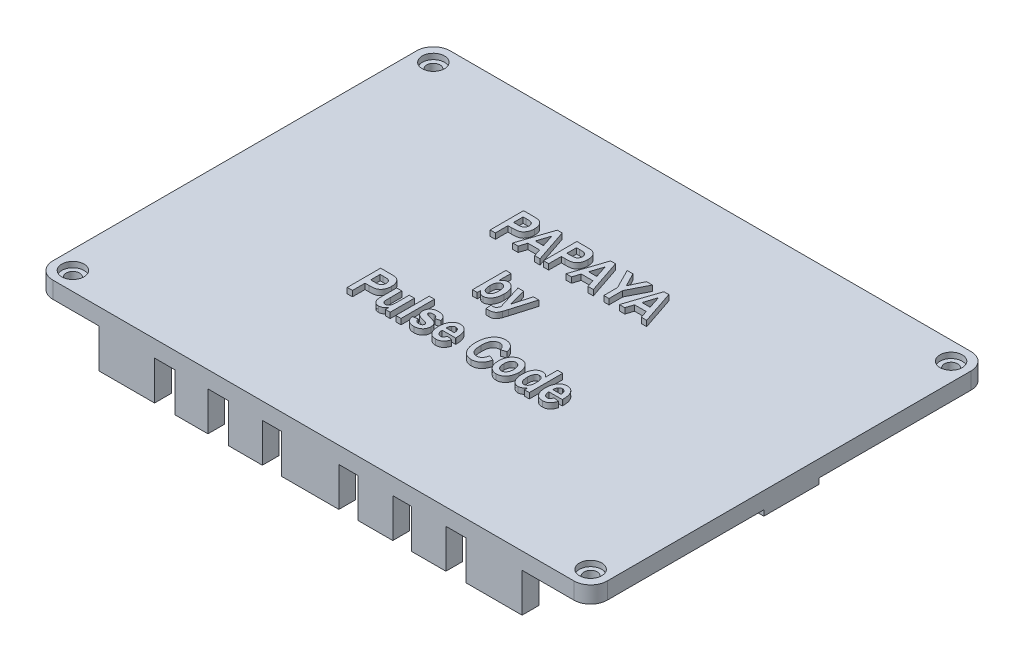
SolidWorks part; units mm, degrees
ref_plane "Front Plane" through (0, 0, 0) normal (0, 0, 1) x (1, 0, 0)
ref_plane "Top Plane" through (0, 0, 0) normal (0, 1, 0) x (1, 0, 0)
ref_plane "Right Plane" through (0, 0, 0) normal (1, 0, 0) x (0, 0, -1)
sketch "Sketch1" plane through (0, 0, 0) normal (0, 1, 0) x (1, 0, 0)
  line L0 (-48.075, 35.695) -> (-51.575, 35.695)
  line L1 (-48.075, 35.695) -> (48.075, 35.695)
  line L3 (-48.075, -35.695) -> (48.075, -35.695)
  line L4 (48.075, 35.695) -> (48.075, -35.695)
  line L5 (-48.075, 35.695) -> (48.075, -35.695) construction
  line L6 (-48.075, -35.695) -> (48.075, 35.695) construction
  line L7 (-51.575, 35.695) -> (-51.575, -35.695)
  line L8 (-51.575, -35.695) -> (-48.075, -35.695)
  point P0 (0, 0)
  dimension "D1" = 96.15
  dimension "D2" = 71.39
  dimension "D3" = 3.5
extrude "Boss-Extrude1" add sketch "Sketch1" along normal blind 3
sketch "Sketch2" plane through (0, 3, 0) normal (0, 1, 0) x (1, 0, 0)
  line L0 (-51.575, -35.695) -> (48.075, -35.695) construction
  line L1 (-40.285, -35.695) -> (-30.295, -35.695)
  line L2 (-40.285, -35.695) -> (-40.285, -32.695)
  line L3 (-40.285, -32.695) -> (-30.295, -32.695)
  line L4 (-30.295, -35.695) -> (-30.295, -32.695)
  line L5 (-51.575, 35.695) -> (-51.575, -35.695) construction
  line L6 (-26.595, -35.695) -> (-20.705, -35.695)
  line L7 (-26.595, -35.695) -> (-26.595, -32.695)
  line L8 (-26.595, -32.695) -> (-20.705, -32.695)
  line L9 (-20.705, -35.695) -> (-20.705, -32.695)
  line L10 (-16.975, -35.695) -> (-10.925, -35.695)
  line L11 (-16.975, -35.695) -> (-16.975, -32.695)
  line L12 (-16.975, -32.695) -> (-10.925, -32.695)
  line L13 (-10.925, -35.695) -> (-10.925, -32.695)
  line L14 (-7.465, -35.695) -> (2.825, -35.695)
  line L15 (-7.465, -35.695) -> (-7.465, -32.695)
  line L16 (-7.465, -32.695) -> (2.825, -32.695)
  line L17 (2.825, -35.695) -> (2.825, -32.695)
  line L18 (6.255, -35.695) -> (12.515, -35.695)
  line L19 (6.255, -35.695) -> (6.255, -32.695)
  line L20 (6.255, -32.695) -> (12.515, -32.695)
  line L21 (12.515, -35.695) -> (12.515, -32.695)
  line L22 (15.865, -35.695) -> (22.065, -35.695)
  line L23 (15.865, -35.695) -> (15.865, -32.695)
  line L24 (15.865, -32.695) -> (22.065, -32.695)
  line L25 (22.065, -35.695) -> (22.065, -32.695)
  line L27 (25.675, -32.695) -> (35.755, -32.695)
  line L28 (25.675, -32.695) -> (25.675, -35.695)
  line L29 (25.675, -35.695) -> (35.755, -35.695)
  line L30 (35.755, -32.695) -> (35.755, -35.695)
  line L31 (48.075, 35.695) -> (-51.575, 35.695) construction
  line L32 (-40.245, 35.695) -> (-34.345, 35.695)
  line L33 (-40.245, 35.695) -> (-40.245, 32.695)
  line L34 (-40.245, 32.695) -> (-34.345, 32.695)
  line L35 (-34.345, 35.695) -> (-34.345, 32.695)
  line L37 (-30.665, 35.695) -> (-22.675, 35.695)
  line L38 (-30.665, 35.695) -> (-30.665, 32.695)
  line L39 (-30.665, 32.695) -> (-22.675, 32.695)
  line L40 (-22.675, 35.695) -> (-22.675, 32.695)
  line L41 (-18.835, 35.695) -> (-10.845, 35.695)
  line L42 (-18.835, 35.695) -> (-18.835, 32.695)
  line L43 (-18.835, 32.695) -> (-10.845, 32.695)
  line L44 (-10.845, 35.695) -> (-10.845, 32.695)
  line L45 (-7.065, 35.695) -> (0.785, 35.695)
  line L46 (-7.065, 35.695) -> (-7.065, 32.695)
  line L47 (-7.065, 32.695) -> (0.785, 32.695)
  line L48 (0.785, 35.695) -> (0.785, 32.695)
  line L49 (4.555, 35.695) -> (12.475, 35.695)
  line L50 (4.555, 35.695) -> (4.555, 32.695)
  line L51 (4.555, 32.695) -> (12.475, 32.695)
  line L52 (12.475, 35.695) -> (12.475, 32.695)
  line L53 (16.385, 35.695) -> (22.465, 35.695)
  line L54 (16.385, 35.695) -> (16.385, 32.695)
  line L55 (16.385, 32.695) -> (22.465, 32.695)
  line L56 (22.465, 35.695) -> (22.465, 32.695)
  point P32 (-16.975, -34.195)
  point P33 (-7.465, -34.195)
  point P60 (-7.065, 34.195)
  point P61 (4.555, 34.195)
  point P62 (16.385, 34.195)
  dimension "D1" = 3
  dimension "D2" = 3
  dimension "D3" = 3
  dimension "D4" = 3
  dimension "D5" = 3
  dimension "D6" = 3
  dimension "D7" = 11.29
  dimension "D8" = 9.99
  dimension "D9" = 3.7
  dimension "D10" = 5.89
  dimension "D11" = 3.73
  dimension "D12" = 6.05
  dimension "D13" = 3.46
  dimension "D14" = 10.29
  dimension "D15" = 3.43
  dimension "D16" = 6.26
  dimension "D17" = 3.35
  dimension "D18" = 6.2
  dimension "D19" = 3.61
  dimension "D20" = 10.08
  dimension "D21" = 3
  dimension "D22" = 3
  dimension "D23" = 11.33
  dimension "D24" = 5.9
  dimension "D25" = 3.68
  dimension "D26" = 7.99
  dimension "D27" = 3.84
  dimension "D28" = 7.99
  dimension "D29" = 3.78
  dimension "D30" = 7.85
  dimension "D31" = 3.77
  dimension "D32" = 7.92
  dimension "D33" = 3.91
  dimension "D34" = 6.08
extrude "Boss-Extrude2" add sketch "Sketch2" against normal blind 10
sketch "Sketch3" plane through (0, 3, 0) normal (0, 1, 0) x (1, 0, 0)
  line L0 (48.075, -35.695) -> (48.075, 35.695) construction
  line L1 (48.075, 5.355) -> (45.075, 5.355)
  line L2 (48.075, 5.355) -> (48.075, -4.555)
  line L3 (48.075, -4.555) -> (45.075, -4.555)
  line L4 (45.075, 5.355) -> (45.075, -4.555)
  line L5 (-51.575, -35.695) -> (48.075, -35.695) construction
  dimension "D1" = 9.91
  dimension "D2" = 3
  dimension "D3" = 31.14
extrude "Boss-Extrude3" add sketch "Sketch3" against normal blind 4
fillet "Fillet1" radius 3 4 edges at (48.075, 1.5, -35.695) (48.075, 1.5, 35.695) (-51.575, 1.5, -35.695) (-51.575, 1.5, 35.695)
sketch "Sketch4" plane through (0, 3, 0) normal (0, 1, 0) x (1, 0, 0)
  text T0 "<b>  PAPAYA </b>\r\n<b>      by</b>\r\n<b>Pulse Code</b>" font "Arial Narrow" height 6
extrude "Boss-Extrude4" add sketch "Sketch4" along normal blind 1
ref_plane "Plane1" through (-1.75, 0, 0) normal (-1, 0, 0) x (0, 0, 1)
ref_plane "Plane2" through (0, 0, 0) normal (0, 0, -1) x (-1, 0, 0)
sketch "Sketch6" plane through (0, 3, 0) normal (0, 1, 0) x (1, 0, 0)
  line L0 (-1.75, 2.2) -> (-1.75, -2.2) construction
  line L1 (5.5, 0) -> (-5.5, 0) construction
  line L2 (-51.575, 32.695) -> (-51.575, -32.695) construction
  line L3 (-48.575, -35.695) -> (45.075, -35.695) construction
  circle A0 centre (-48.275, -32.395) radius 1.2
  circle A1 centre (44.775, -32.395) radius 1.2
  circle A2 centre (44.775, 32.395) radius 1.2
  circle A3 centre (-48.275, 32.395) radius 1.2
  dimension "D1" = 3.3
  dimension "D2" = 3.3
extrude "Cut-Extrude1" cut sketch "Sketch6" against normal up to next
sketch "Sketch7" plane through (0, 3, 0) normal (0, 1, 0) x (1, 0, 0)
  line L0 (-1.75, 2.2) -> (-1.75, -2.2) construction
  line L1 (5.5, 0) -> (-5.5, 0) construction
  circle A0 centre (-48.275, -32.395) radius 2
  circle A1 centre (44.775, -32.395) radius 2
  circle A2 centre (44.775, 32.395) radius 2
  circle A3 centre (-48.275, 32.395) radius 2
extrude "Cut-Extrude2" cut sketch "Sketch7" against normal blind 1
